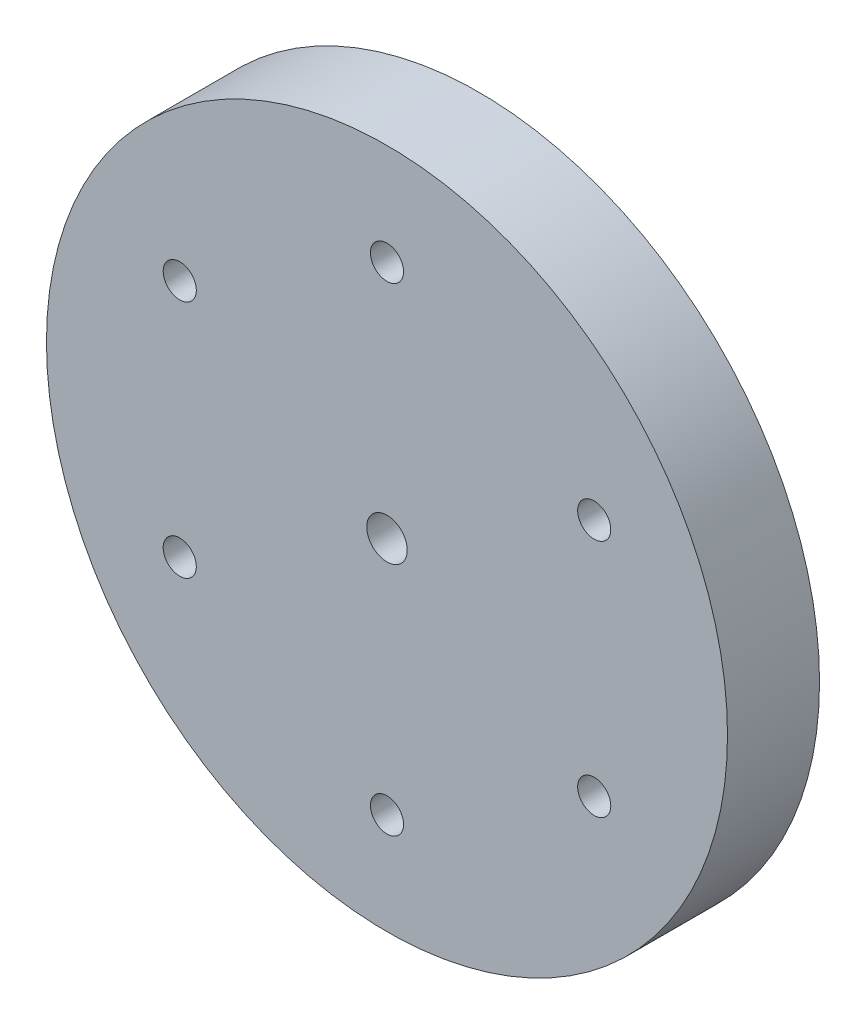
SolidWorks part; units mm, degrees
ref_plane "前视基准面" through (0, 0, 0) normal (0, 0, 1) x (1, 0, 0)
ref_plane "上视基准面" through (0, 0, 0) normal (0, 1, 0) x (1, 0, 0)
ref_plane "右视基准面" through (0, 0, 0) normal (1, 0, 0) x (0, 0, -1)
other "Configuration Table"
sketch "草图1" plane through (0, 0, 0) normal (0, 0, 1) x (1, 0, 0)
  circle A2 centre (0, 0) radius 18.5
  circle A3 centre (0, 0) radius 17.5
  circle A4 centre (0, 0) radius 1.1
  dimension "D1" = 37
  dimension "D2" = 35
  dimension "D3" = 2.2
extrude "凸台-拉伸1" add sketch "草图1" along normal mid plane 5
sketch "草图2" plane through (0, 0, 2.5) normal (0, 0, 1) x (1, 0, 0)
  circle A0 centre (0, 13) radius 0.9
  dimension "D1" = 1.8
  dimension "D2" = 13
extrude "切除-拉伸1" cut sketch "草图2" against normal through all
pattern_circular "阵列(圆周)1" count 6 over 360 about axis through (0, 0, 0) along (0, 0, 1) of "切除-拉伸1"
